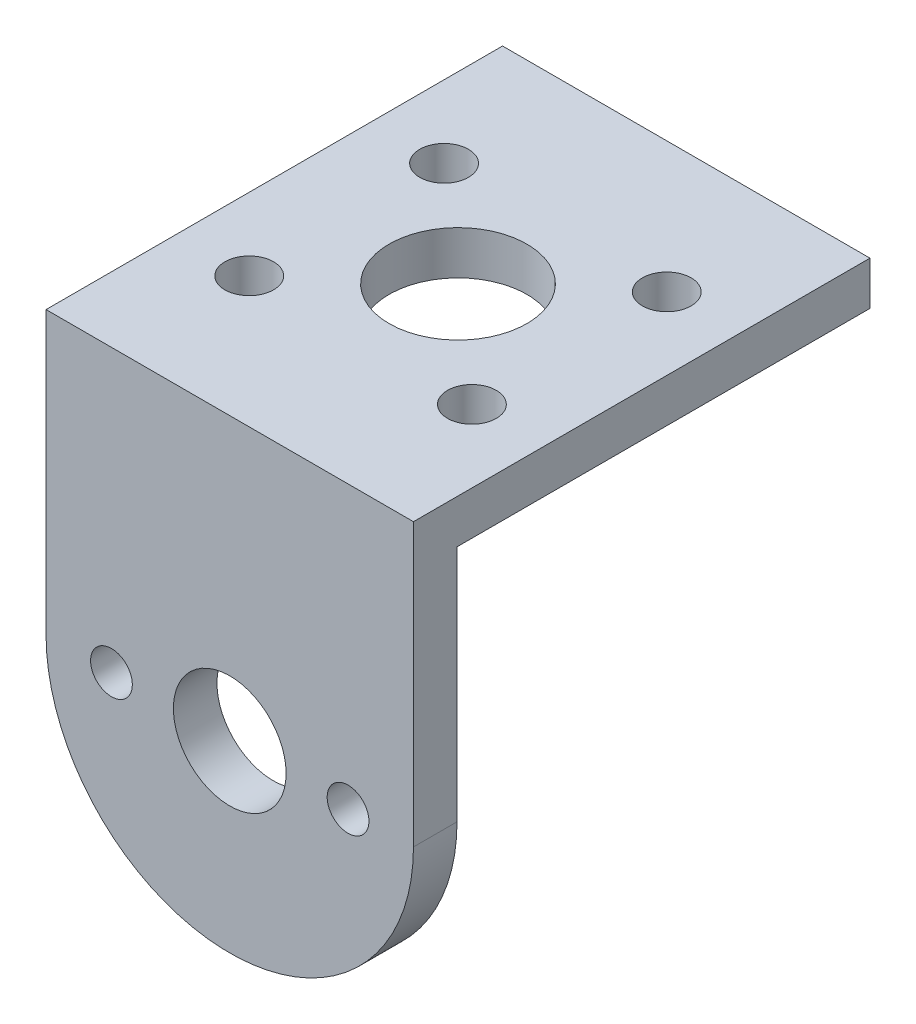
SolidWorks part; units mm, degrees
ref_plane "Front Plane" through (0, 0, 0) normal (0, 0, 1) x (1, 0, 0)
ref_plane "Top Plane" through (0, 0, 0) normal (0, 1, 0) x (1, 0, 0)
ref_plane "Right Plane" through (0, 0, 0) normal (1, 0, 0) x (0, 0, -1)
sketch "Sketch1" plane through (0, 0, 0) normal (0, 0, 1) x (1, 0, 0)
  line L0 (0, 0) -> (0, -13.2) construction
  line L1 (-13.2, 20.24) -> (13.2, 20.24)
  line L2 (-13.2, 20.24) -> (-13.2, 0)
  line L3 (-13.2, 0) -> (13.2, 0)
  line L4 (13.2, 20.24) -> (13.2, 0)
  circle A0 centre (0, 0) radius 13.2
  dimension "D1" = 26.4
  dimension "D2" = 33.44
extrude "Boss-Extrude1" add sketch "Sketch1" against normal blind 3.13 contours A0 L4 L1 L2 | L3 A0 | L3 L0 A0 | L0 L3 A0
sketch "Sketch2" plane through (0, 0, 0) normal (0, 0, 1) x (1, 0, 0)
  circle A0 centre (0, 0) radius 4.05
  dimension "D1" = 8.1
extrude "Cut-Extrude1" cut sketch "Sketch2" against normal blind 3.13 contours A0
sketch "Sketch3" plane through (0, 0, 0) normal (0, 0, 1) x (1, 0, 0)
  line L0 (0, 0) -> (8.5, 0) construction
  line L1 (0, 0) -> (-8.5, 0) construction
  circle A0 centre (0, 0) radius 8.5 construction
  circle A1 centre (8.5, 0) radius 1.5
  circle A2 centre (-8.5, 0) radius 1.5
  dimension "D1" = 17
  dimension "D2" = 3
extrude "Cut-Extrude2" cut sketch "Sketch3" against normal blind 17 contours A2 | A1
sketch "Sketch4" plane through (0, 20.24, 0) normal (0, 1, 0) x (1, 0, 0)
  line L1 (-13.2, 0) -> (13.2, 0)
  line L2 (-13.2, 0) -> (-13.2, 32.8)
  line L3 (-13.2, 32.8) -> (13.2, 32.8)
  line L4 (13.2, 0) -> (13.2, 32.8)
  dimension "D1" = 32.8
extrude "Boss-Extrude2" add sketch "Sketch4" against normal blind 3.13 contours L2 L1 L4 L3
sketch "Sketch5" plane through (0, 20.24, 0) normal (0, 1, 0) x (1, 0, 0)
  line L0 (0, 32.8) -> (0, 0) construction
  line L1 (-13.2, 32.8) -> (13.2, 32.8) construction
  line L2 (-13.2, 16.4) -> (13.2, 16.4) construction
  line L3 (-13.2, 32.8) -> (-13.2, 0) construction
  line L4 (13.2, 32.8) -> (13.2, 0) construction
  circle A0 centre (0, 16.4) radius 4.95
  dimension "D1" = 9.9
extrude "Cut-Extrude3" cut sketch "Sketch5" against normal blind 3.13 contours A0
sketch "Sketch6" plane through (0, 20.24, 0) normal (0, 1, 0) x (1, 0, 0)
  line L0 (0, 23.4) -> (0, 9.4) construction
  line L1 (-8, 23.4) -> (8, 23.4) construction
  line L2 (-8, 23.4) -> (-8, 9.4) construction
  line L3 (-8, 9.4) -> (8, 9.4) construction
  line L4 (8, 23.4) -> (8, 9.4) construction
  line L5 (8, 16.4) -> (-8, 16.4) construction
  circle A0 centre (0, 16.4) radius 4.95 construction
  circle A1 centre (8, 23.4) radius 1.75
  circle A2 centre (8, 9.4) radius 1.75
  circle A3 centre (-8, 9.4) radius 1.75
  circle A4 centre (-8, 23.4) radius 1.75
  point P8 (0, 16.4)
  dimension "D3" = 3.5
  dimension "D1" = 14
  dimension "D2" = 16
extrude "Cut-Extrude4" cut sketch "Sketch6" against normal blind 3.13
